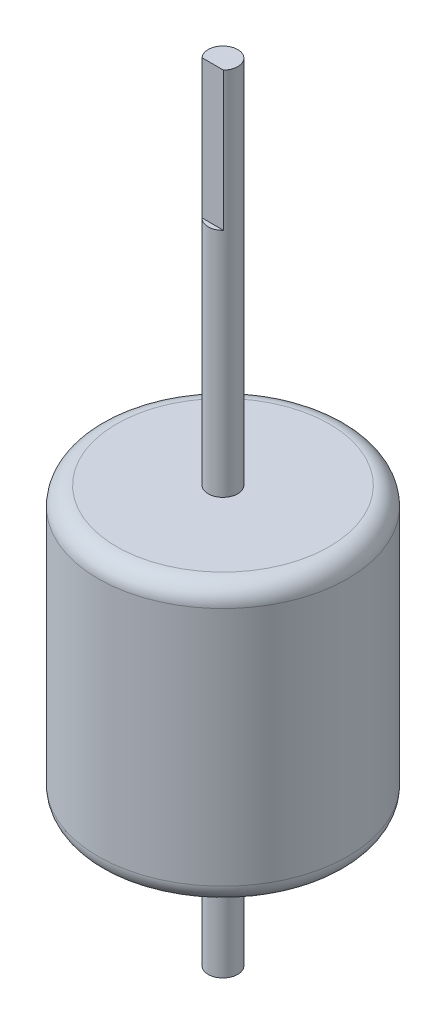
SolidWorks part; units mm, degrees
material "Cuivre"
ref_plane "Plan de face" through (0, 0, 0) normal (0, 0, 1) x (1, 0, 0)
ref_plane "Plan de dessus" through (0, 0, 0) normal (0, 1, 0) x (1, 0, 0)
ref_plane "Plan de droite" through (0, 0, 0) normal (1, 0, 0) x (0, 0, -1)
sketch "Esquisse1" plane through (0, 0, 0) normal (0, 0, 1) x (1, 0, 0)
  line L0 (0, 0) -> (0, 85) construction
  line L1 (0, 0) -> (-1.6, 0)
  line L2 (-1.6, 0) -> (-1.6, 2.6)
  line L3 (-1.6, 2.6) -> (-5.075, 2.6)
  line L4 (-5.075, 2.6) -> (-5.075, 4.5)
  line L5 (-5.075, 4.5) -> (-19, 4.5)
  line L6 (-19, 4.5) -> (-19, 58)
  line L7 (-19, 58) -> (-17.85, 58)
  line L8 (-17.85, 58) -> (-17.85, 60)
  line L9 (-16.35, 61.5) -> (-6.5, 61.5)
  line L10 (-6.5, 61.5) -> (-6.5, 65.8)
  line L11 (-6.5, 65.8) -> (-1.6, 65.8)
  line L12 (-1.6, 65.8) -> (-1.6, 85)
  line L13 (-1.6, 85) -> (0, 85)
  line L14 (0, 0) -> (0, 85)
  arc A0 (-17.85, 60) -> (-16.35, 61.5) centre (-16.35, 60) cw
  dimension "D13" = 1.5
  dimension "D1" = 3.2
  dimension "D2" = 2.6
  dimension "D3" = 10.15
  dimension "D4" = 4.5
  dimension "D5" = 38
  dimension "D6" = 53.5
  dimension "D7" = 35.7
  dimension "D8" = 57
  dimension "D9" = 13
  dimension "D10" = 4.3
  dimension "D11" = 3.2
  dimension "D12" = 85
revolve "Révolution1" add sketch "Esquisse1" angle 360 about L0
sketch "Esquisse2" plane through (0, 85, 0) normal (0, 1, 0) x (1, 0, 0)
  line L0 (-1.1619, -1.1) -> (1.1619, -1.1)
  circle A1 centre (0, 0) radius 1.6
  arc A2 (-1.1619, -1.1) -> (1.1619, -1.1) centre (0, 0) ccw
  dimension "D2" = 1.1
  dimension "D1" = 0
extrude "Enlèv. mat.-Extru.1" cut sketch "Esquisse2" against normal blind 15
hole_wizard "Trou taraudé M31" positions "Esquisse4" profile "Esquisse3" tap size "M3" standard "ISO"
sketch "Esquisse4" plane through (0, 61.5, 0) normal (0, 1, 0) x (-1, 0, 0)
  point P0 (12.5, 0)
  point P1 (-12.5, 0)
  dimension "D1" = 25
  dimension "D2" = 12.5
sketch "Esquisse3" plane through (-12.5, 61.5, 0) normal (1, 0, 0) x (0, 0, 1)
  line L0 (0, 0) -> (0, 9.2511)
  line L1 (0, 9.2511) -> (1.25, 8.5)
  line L2 (1.25, 8.5) -> (1.25, 0)
  line L5 (1.25, 0) -> (0, 0)
  line L10 (0, 9.2511) -> (-1.25, 8.5) construction
  line L11 (0, -6.35) -> (0, 107.95) construction
  dimension "Diamètre du trou pour taraudage" = 2.5
  dimension "Profondeur du trou pour taraudage" = 8.5
  dimension "Angle de pointe" = 118
cosmetic thread "Filetage de perçage1" parameters "D1"=6, "D2"=3
cosmetic thread "Filetage de perçage2" parameters "D1"=6, "D2"=3
sketch "Esquisse5" plane through (0, 4.5, 0) normal (0, -1, 0) x (1, 0, 0)
  line L1 (-14.3, 1.9) -> (-13.6, 1.9)
  line L2 (-14.3, 1.9) -> (-14.3, -1.9)
  line L3 (-14.3, -1.9) -> (-13.6, -1.9)
  line L4 (-13.6, 1.9) -> (-13.6, -1.9)
  dimension "D1" = 14.3
  dimension "D2" = 0.7
  dimension "D3" = 3.8
  dimension "D4" = 1.9
extrude "Boss.-Extru.1" add sketch "Esquisse5" along normal blind 6.7
chamfer "Chanfrein1" distance 1 angle 45 2 edges at (-13.95, -2.2, 1.9) (-13.95, -2.2, -1.9)
sketch "Esquisse6" plane through (-14.3, 0, 0) normal (-1, 0, 0) x (0, 0, 1)
  circle A0 centre (0, 0) radius 0.8
  dimension "D1" = 1.6
extrude "Enlèv. mat.-Extru.2" cut sketch "Esquisse6" against normal blind 6.7
pattern_circular "Répétition circulaire1" count 2 over 360 about axis through (0, 0, 0) along (0, 1, 0) of "Enlèv. mat.-Extru.2", "Boss.-Extru.1", "Chanfrein1"
sketch "Esquisse7" plane through (0, 0, 0) normal (0, -1, 0) x (1, 0, 0)
  circle A0 centre (0, 0) radius 19 construction
  circle A1 centre (0, 0) radius 19
  circle A2 centre (0, 0) radius 1.6 construction
  circle A3 centre (0, 0) radius 1.6
extrude "Enlèv. mat.-Extru.4" cut sketch "Esquisse7" against normal through all and the other way through all
ref_plane "Plan1" through (0, 20, 0) normal (0, -1, 0) x (1, 0, 0)
sketch "Esquisse9" plane through (0, 0, 0) normal (0, 0, 1) x (1, 0, 0)
  line L0 (0, 0) -> (0, 86.9771) construction
  line L1 (0, 15) -> (11.5, 15)
  line L2 (13.5, 17) -> (13.5, 43)
  line L3 (11.5, 45) -> (0, 45)
  line L4 (-1.6, 0) -> (1.6, 0) construction
  line L5 (0, 44.5) -> (0, 45)
  line L6 (0, 44.5) -> (10, 44.5)
  line L8 (0, 15.5) -> (10, 15.5)
  line L9 (0, 15) -> (0, 15.5)
  line L10 (10, 44.5) -> (10, 15.5)
  arc A0 (11.5, 15) -> (13.5, 17) centre (11.5, 17) ccw
  arc A1 (13.5, 43) -> (11.5, 45) centre (11.5, 43) ccw
  point P13 (0, 15.2)
  point P14 (3.5, 15.2)
  point P15 (3.5, 23)
  point P16 (11.3, 23)
  point P17 (11.3, 37)
  point P18 (3.5, 37)
  point P19 (3.5, 44.8)
  point P20 (0, 44.8)
  dimension "D1" = 2
  dimension "D2" = 27
  dimension "D3" = 30
  dimension "D4" = 15
  dimension "D6" = 0.5
  dimension "D5" = 0.5
  dimension "D7" = 20
revolve "Révolution2" add sketch "Esquisse9" angle 360 about L0
